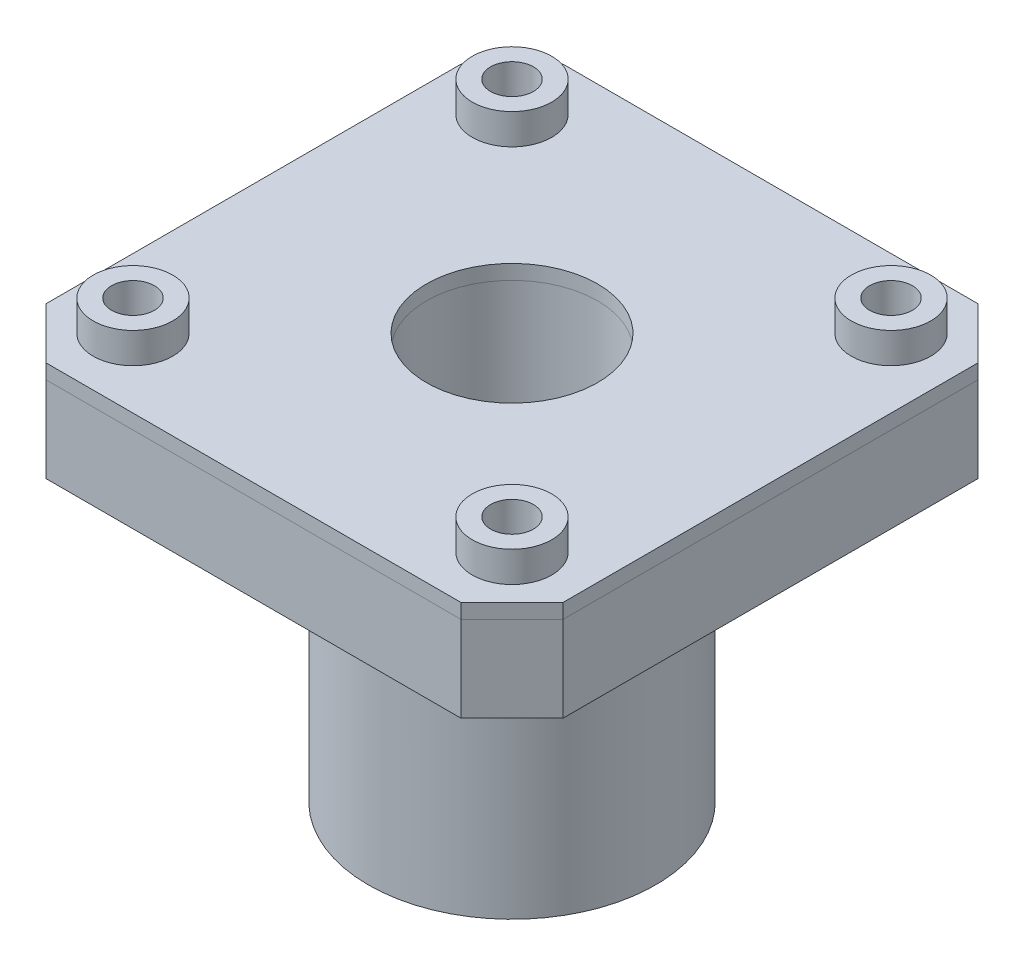
SolidWorks part; units mm, degrees
ref_plane "Front Plane" through (0, 0, 0) normal (0, 0, 1) x (1, 0, 0)
ref_plane "Top Plane" through (0, 0, 0) normal (0, 1, 0) x (1, 0, 0)
ref_plane "Right Plane" through (0, 0, 0) normal (1, 0, 0) x (0, 0, -1)
sketch "Sketch1" plane through (0, 0, 0) normal (0, 1, 0) x (1, 0, 0)
  line L1 (-21.15, 21.15) -> (21.15, 21.15)
  line L2 (-21.15, 21.15) -> (-21.15, -21.15)
  line L3 (-21.15, -21.15) -> (21.15, -21.15)
  line L4 (21.15, 21.15) -> (21.15, -21.15)
  line L5 (-21.15, 21.15) -> (21.15, -21.15) construction
  line L6 (-21.15, -21.15) -> (21.15, 21.15) construction
  point P0 (0, 0)
  dimension "D1" = 42.3
extrude "Boss-Extrude1" add sketch "Sketch1" along normal blind 8.2
ref_plane "Plane1" through (0, 0.8, 0) normal (0, -1, 0) x (-1, 0, 0)
sketch "Sketch4" plane through (0, 0, 0) normal (0, 1, 0) x (1, 0, 0)
  line L0 (-21.15, 16.9631) -> (-16.9631, 21.15)
  line L1 (-21.15, 21.15) -> (-21.15, -21.15) construction
  line L2 (21.15, 21.15) -> (-21.15, 21.15) construction
  line L3 (16.9631, -21.15) -> (21.15, -16.9631)
  line L4 (-21.15, -21.15) -> (21.15, -21.15) construction
  line L5 (21.15, -21.15) -> (21.15, 21.15) construction
  line L6 (-21.15, 16.9631) -> (-21.15, 21.15)
  line L7 (-21.15, 21.15) -> (-16.9631, 21.15)
  line L8 (21.15, -16.9631) -> (21.15, -21.15)
  line L9 (21.15, -21.15) -> (16.9631, -21.15)
  dimension "D1" = 53.9
  dimension "D2" = 45
extrude "Cut-Extrude3" cut sketch "Sketch4" against normal through all and the other way through all
mirror "Mirror1" about plane through (0, 0, 0) normal (0, 0, 1) of "Cut-Extrude3"
sketch "Sketch6" plane through (0, 8.2, 0) normal (0, 1, 0) x (1, 0, 0)
  circle A0 centre (-15.5, 15.5) radius 3.25
  dimension "D1" = 6.5
  dimension "D2" = 15.5
  dimension "D3" = 15.5
extrude "Boss-Extrude2" add sketch "Sketch6" along normal blind 2.5
sketch "Sketch7" plane through (0, 0, 0) normal (0, 1, 0) x (1, 0, 0)
  circle A0 centre (-15.5, 15.5) radius 1.75
  dimension "D1" = 3.5
extrude "Cut-Extrude6" cut sketch "Sketch7" along normal through all
sketch "Sketch10" plane through (0, 0, 0) normal (0, 1, 0) x (-1, 0, 0)
  circle A0 centre (15.5, -15.5) radius 3
  circle A1 centre (15.5, -15.5) radius 1.75 construction
  dimension "D1" = 6
extrude "Cut-Extrude9" cut sketch "Sketch10" along normal blind 3.25
mirror "Mirror4" about plane through (0, 0, 0) normal (1, 0, 0) of "Cut-Extrude9", "Boss-Extrude2", "Cut-Extrude6"
mirror "Mirror5" about plane through (0, 0, 0) normal (0, 0, 1) of "Mirror4", "Boss-Extrude2", "Cut-Extrude6", "Cut-Extrude9"
sketch "Sketch11" plane through (0, 0, 0) normal (0, -1, 0) x (1, 0, 0)
  circle A0 centre (0, 0) radius 11.75
  dimension "D1" = 23.5
extrude "Boss-Extrude3" add sketch "Sketch11" along normal blind 25
sketch "Sketch2" plane through (0, -25, 0) normal (0, -1, 0) x (-1, 0, 0)
  line L0 (-16.9631, 21.15) -> (16.9631, 21.15) construction
  line L1 (11.0851, 0) -> (5.5426, 9.6)
  line L2 (5.5426, 9.6) -> (-5.5426, 9.6)
  line L3 (-5.5426, 9.6) -> (-11.0851, 0)
  line L4 (-11.0851, 0) -> (-5.5426, -9.6)
  line L5 (-5.5426, -9.6) -> (5.5426, -9.6)
  line L6 (5.5426, -9.6) -> (11.0851, 0)
  circle A0 centre (0, 0) radius 9.6 construction
  dimension "D1" = 19.2
extrude "Cut-Extrude10" cut sketch "Sketch2" against normal blind 6.2 from offset 1 offset against normal yes
sketch "Sketch8" plane through (0, -25, 0) normal (0, 1, 0) x (1, 0, 0)
  circle A0 centre (0, 0) radius 7
  dimension "D1" = 14
extrude "Cut-Extrude11" cut sketch "Sketch8" along normal through all
sketch "Sketch12" plane through (0, 8.2, 0) normal (0, 1, 0) x (1, 0, 0)
  circle A0 centre (0, 0) radius 2.5
  dimension "D1" = 5
ref_plane "Plane2" through (0, 7, 0) normal (0, -1, 0) x (-1, 0, 0)
split "Split1" trim tools "Plane2" bodies to split 118 resulting bodies 120 121
